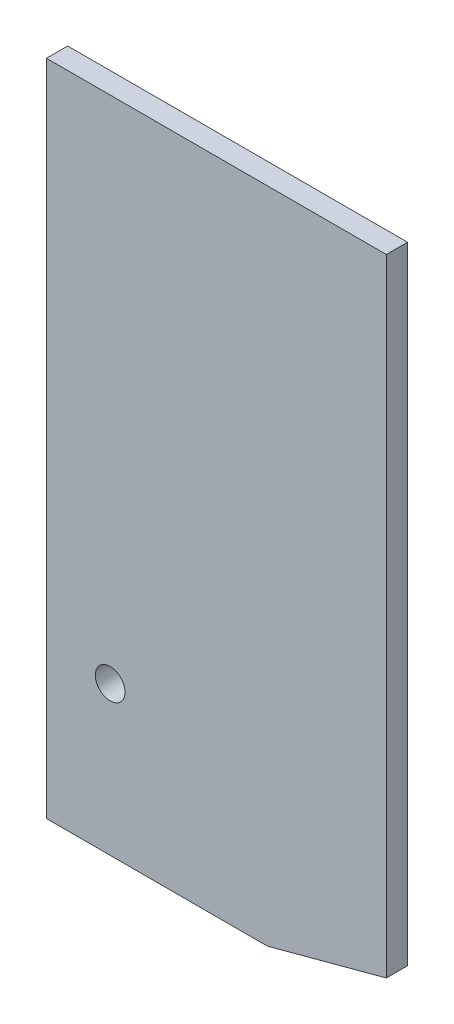
SolidWorks part; units mm, degrees
ref_plane "Plan de face" through (0, 0, 0) normal (0, 0, 1) x (1, 0, 0)
ref_plane "Plan de dessus" through (0, 0, 0) normal (0, 1, 0) x (1, 0, 0)
ref_plane "Plan de droite" through (0, 0, 0) normal (1, 0, 0) x (0, 0, -1)
sketch "Esquisse1" plane through (0, 0, 0) normal (0, 0, 1) x (1, 0, 0)
  line L0 (52.0096, 0) -> (80, 7.5)
  line L1 (0, 0) -> (52.0096, 0)
  line L2 (0, 0) -> (0, 155)
  line L3 (0, 155) -> (80, 155)
  line L4 (80, 7.5) -> (80, 155)
  circle A0 centre (15, 35) radius 3.5
  dimension "D6" = 7
  dimension "D7" = 35
  dimension "D8" = 15
  dimension "D1" = 80
  dimension "D2" = 155
  dimension "D3" = 15
  dimension "D4" = 7.5
  dimension "D5" = 27.9904
extrude "Boss.-Extru.1" add sketch "Esquisse1" along normal blind 5
